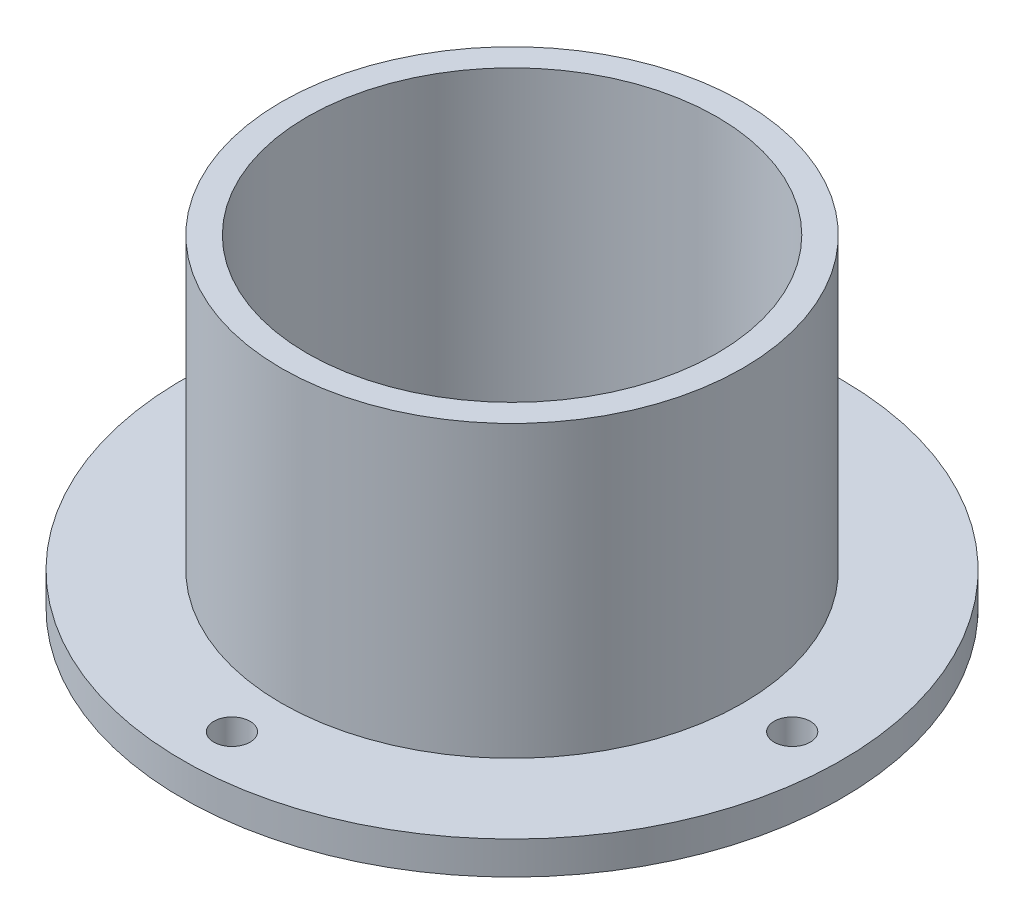
SolidWorks part; units mm, degrees
ref_plane "Front Plane" through (0, 0, 0) normal (0, 0, 1) x (1, 0, 0)
ref_plane "Top Plane" through (0, 0, 0) normal (0, 1, 0) x (1, 0, 0)
ref_plane "Right Plane" through (0, 0, 0) normal (1, 0, 0) x (0, 0, -1)
sketch "Sketch1" plane through (0, 0, 0) normal (0, 1, 0) x (1, 0, 0)
  circle A0 centre (0, 0) radius 35
  dimension "D1" = 70
extrude "Boss-Extrude1" add sketch "Sketch1" along normal blind 9
sketch "Sketch4" plane through (0, 0, 0) normal (0, -1, 0) x (1, 0, 0)
  circle A0 centre (0, 0) radius 31.0832
extrude "Cut-Extrude1" cut sketch "Sketch4" against normal blind 9
sketch "Sketch5" plane through (0, 0, 0) normal (0, -1, 0) x (1, 0, 0)
  circle A0 centre (0, 0) radius 35
  circle A1 centre (0, 0) radius 31.0832
  dimension "D1" = 70
  dimension "D2" = 62.1664
extrude "Boss-Extrude3" add sketch "Sketch5" along normal blind 40
sketch "Sketch8" plane through (0, -40, 0) normal (0, -1, 0) x (1, 0, 0)
  circle A1 centre (0, 0) radius 50
  circle A4 centre (0, 0) radius 35 construction
  dimension "D1" = 15
extrude "Boss-Extrude4" add sketch "Sketch8" against normal blind 5
sketch "Sketch10" plane through (0, -35, 0) normal (0, 1, 0) x (1, 0, 0)
  circle A0 centre (0, 42.5) radius 2.75
  circle A1 centre (0, 0) radius 42.5 construction
  circle A2 centre (0, 0) radius 50 construction
  circle A3 centre (42.5, 0) radius 2.75
  circle A4 centre (0, -42.5) radius 2.75
  circle A5 centre (-42.5, 0) radius 2.75
  point P16 (0, 0)
  dimension "D1" = 5.5
  dimension "D2" = 7.5
  dimension "D3" = 4
extrude "Cut-Extrude2" cut sketch "Sketch10" against normal blind 5
sketch "Sketch11" plane through (0, -35, 0) normal (0, 1, 0) x (1, 0, 0)
  circle A0 centre (0, 0) radius 31.0832
extrude "Cut-Extrude3" cut sketch "Sketch11" against normal blind 5
